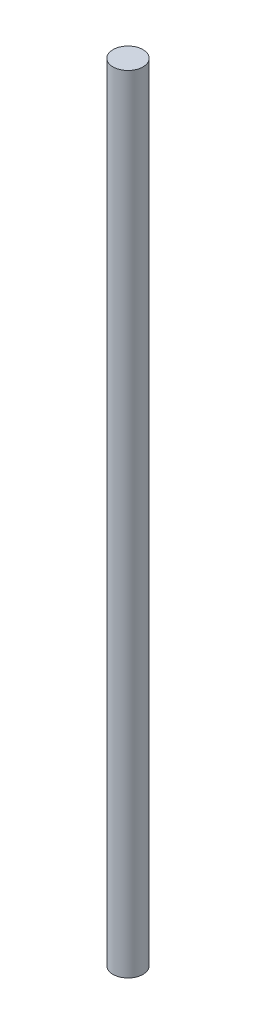
SolidWorks part; units mm, degrees
ref_plane "Front Plane" through (0, 0, 0) normal (0, 0, 1) x (1, 0, 0)
ref_plane "Top Plane" through (0, 0, 0) normal (0, 1, 0) x (1, 0, 0)
ref_plane "Right Plane" through (0, 0, 0) normal (1, 0, 0) x (0, 0, -1)
sketch "Sketch1" plane through (0, 0, 0) normal (0, 1, 0) x (1, 0, 0)
  circle A0 centre (0, 0) radius 7.5
  dimension "D1" = 15
extrude "Boss-Extrude1" add sketch "Sketch1" along normal blind 393
